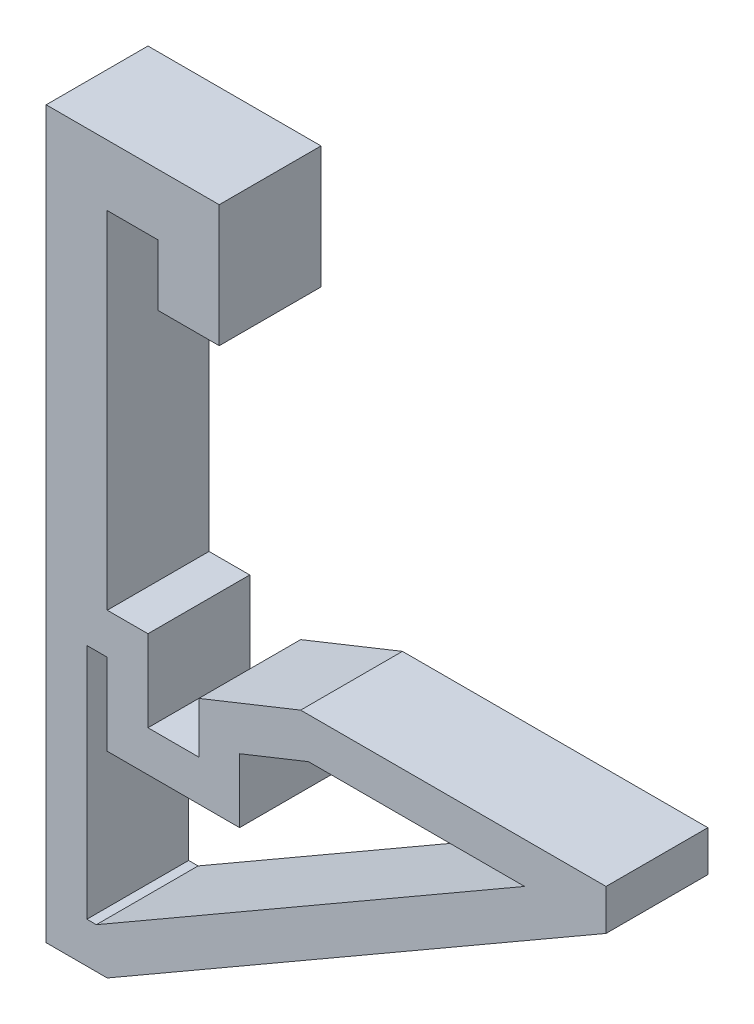
SolidWorks part; units mm, degrees
ref_plane "前视基准面" through (0, 0, 0) normal (0, 0, 1) x (1, 0, 0)
ref_plane "上视基准面" through (0, 0, 0) normal (0, 1, 0) x (1, 0, 0)
ref_plane "右视基准面" through (0, 0, 0) normal (1, 0, 0) x (0, 0, -1)
other "Configuration Table"
sketch "草图1" plane through (0, 0, 0) normal (0, 0, 1) x (1, 0, 0)
  line L0 (0, 0) -> (0, 35.6451)
  line L1 (0, 35.6451) -> (8.5, 35.6451)
  line L2 (8.5, 35.6451) -> (8.5, 29.6451)
  line L3 (8.5, 29.6451) -> (5.5, 29.6451)
  line L4 (5.5, 29.6451) -> (5.5, 32.6451)
  line L5 (5.5, 32.6451) -> (3, 32.6451)
  line L6 (3, 32.6451) -> (3, 15.6451)
  line L13 (3, 0) -> (27.5, 14.1451)
  line L14 (27.5, 14.1451) -> (7.5, 14.1451) construction
  line L15 (7.5, 14.1451) -> (7.5, 11.6451)
  line L16 (7.5, 11.6451) -> (5, 11.6451)
  line L17 (5, 11.6451) -> (5, 15.6451)
  line L18 (5, 15.6451) -> (3, 15.6451)
  line L19 (0, 0) -> (3, 0)
  line L20 (3, 15.6451) -> (0, 15.6451) construction
  line L21 (3, 32.6451) -> (0, 32.6451) construction
  line L22 (27.5, 16.1451) -> (12.5, 16.1451)
  line L23 (27.5, 16.1451) -> (27.5, 14.1451)
  line L24 (12.5, 16.1451) -> (7.5, 14.1451)
  dimension "D1" = 3
  dimension "D2" = 3
  dimension "D3" = 3
  dimension "D4" = 2.5
  dimension "D5" = 2.5
  dimension "D6" = 3
  dimension "D7" = 2.5
  dimension "D8" = 4
  dimension "D9" = 2
  dimension "D10" = 20
  dimension "D11" = 60
  dimension "D12" = 17
  dimension "D13" = 2
  dimension "D14" = 15
extrude "凸台-拉伸1" add sketch "草图1" along normal blind 5
sketch "草图2" plane through (0, 0, 5) normal (0, 0, 1) x (1, 0, 0)
  line L16 (9.5, 12.791) -> (9.5, 9.6451)
  line L18 (9.5, 12.791) -> (9.5, 9.6451)
  line L20 (23.5, 14.1451) -> (12.8852, 14.1451)
  line L21 (23.5, 14.1451) -> (12.8852, 14.1451)
  line L22 (12.8852, 14.1451) -> (9.5, 12.791)
  line L23 (12.8852, 14.1451) -> (9.5, 12.791)
  line L28 (2, 2) -> (2.4641, 2)
  line L29 (2.4641, 2) -> (23.5, 14.1451)
  line L32 (9.5, 9.6451) -> (3, 9.6451)
  line L33 (3, 9.6451) -> (3, 13.6451)
  line L34 (3, 13.6451) -> (2, 13.6451)
  line L35 (2, 13.6451) -> (2, 2)
  line L36 (2, 2) -> (2.4641, 2)
  line L37 (2.4641, 2) -> (23.5, 14.1451)
  line L40 (9.5, 9.6451) -> (3, 9.6451)
  line L41 (3, 9.6451) -> (3, 13.6451)
  line L42 (3, 13.6451) -> (2, 13.6451)
  line L43 (2, 13.6451) -> (2, 2)
  point P0 (0, 0)
  dimension "D1" = 2
extrude "切除-拉伸1" cut sketch "草图2" against normal through all
